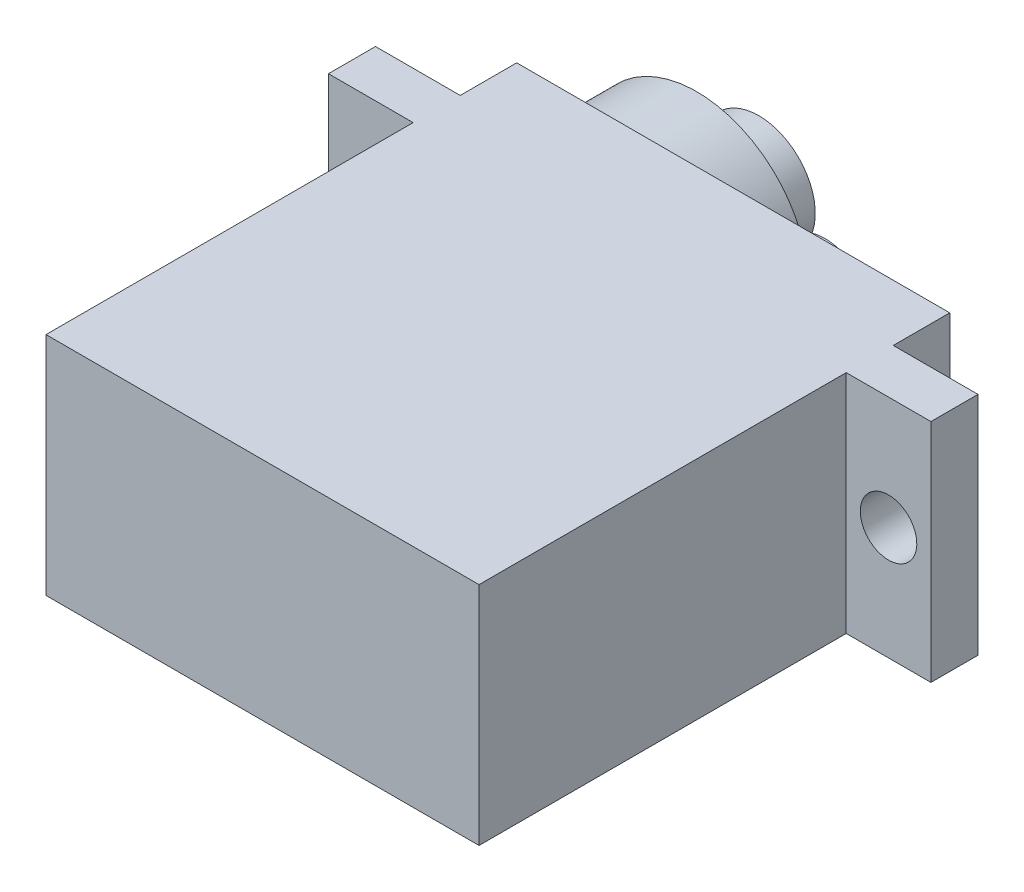
SolidWorks part; units mm, degrees
ref_plane "Front Plane" through (0, 0, 0) normal (0, 0, 1) x (1, 0, 0)
ref_plane "Top Plane" through (0, 0, 0) normal (0, 1, 0) x (1, 0, 0)
ref_plane "Right Plane" through (0, 0, 0) normal (1, 0, 0) x (0, 0, -1)
sketch "Sketch1" plane through (0, 0, 0) normal (0, 0, 1) x (1, 0, 0)
  line L1 (11.5, -6) -> (-11.5, -6)
  line L2 (11.5, -6) -> (11.5, 6)
  line L3 (11.5, 6) -> (-11.5, 6)
  line L4 (-11.5, -6) -> (-11.5, 6)
  line L5 (11.5, -6) -> (-11.5, 6) construction
  line L6 (11.5, 6) -> (-11.5, -6) construction
  point P0 (0, 0)
  dimension "D1" = 23
  dimension "D2" = 12
extrude "Boss-Extrude1" add sketch "Sketch1" along normal blind 25
sketch "Sketch3" plane through (11.5, 0, 0) normal (1, 0, 0) x (0, 0, -1)
  line L0 (-25, 6) -> (0, 6) construction
  line L1 (-3, 6) -> (-5.5, 6)
  line L2 (-3, 6) -> (-3, -6)
  line L3 (-3, -6) -> (-5.5, -6)
  line L4 (-5.5, 6) -> (-5.5, -6)
  line L5 (-25, -6) -> (0, -6) construction
  dimension "D1" = 2.5
  dimension "D2" = 19.5
extrude "Boss-Extrude2" add sketch "Sketch3" along normal blind 4.5
sketch "Sketch4" plane through (-11.5, 0, 0) normal (-1, 0, 0) x (0, 0, 1)
  line L0 (25, 6) -> (0, 6) construction
  line L1 (5.5, 6) -> (3, 6)
  line L2 (5.5, 6) -> (5.5, -6)
  line L3 (5.5, -6) -> (3, -6)
  line L4 (3, 6) -> (3, -6)
  line L5 (25, -6) -> (0, -6) construction
  dimension "D1" = 19.5
  dimension "D2" = 2.5
extrude "Boss-Extrude3" add sketch "Sketch4" along normal blind 4.5
sketch "Sketch5" plane through (0, 0, 0) normal (0, 0, -1) x (-1, 0, 0)
  circle A0 centre (5.443, 0) radius 5.9554
  circle A1 centre (-1.3696, 0.1346) radius 2.4728
  circle A2 centre (5.443, 0) radius 1.9661
extrude "Boss-Extrude13" add sketch "Sketch5" along normal blind 3.5 contours A0 A1 | A1 A0 A2 | A0 A1 | A2
sketch "Sketch7" plane through (0, 0, -3.5) normal (0, 0, -1) x (-1, 0, 0)
  circle A0 centre (5.6429, 0) radius 3
extrude "Boss-Extrude14" add sketch "Sketch7" along normal blind 3.5
sketch "Sketch8" plane through (0, 0, 3) normal (0, 0, -1) x (-1, 0, 0)
  line L4 (13.75, 6) -> (13.75, -7.1508) construction
  line L5 (16, 6) -> (11.5, 6) construction
  line L6 (11.3984, 0) -> (16.9242, 0) construction
  line L9 (-13.75, 6) -> (-13.75, -6.9765) construction
  line L10 (-16, 6) -> (-11.5, 6) construction
  line L13 (-16, -6) -> (-11.5, -6) construction
  arc A1 (-0.1588, -2.0215) -> (-0.0746, 2.2413) centre (5.443, 0) ccw construction
  arc A2 (-0.1588, -2.0215) -> (-0.0746, 2.2413) centre (5.443, 0) ccw construction
  circle A3 centre (13.75, 0) radius 1.5
  circle A4 centre (-13.75, 0) radius 1.5
  dimension "D1" = 6
  dimension "D2" = 3
  dimension "D3" = 3
extrude "Cut-Extrude1" cut sketch "Sketch8" against normal blind 3.5 contours A3 | A4
sketch "Sketch9" plane through (0, -6, 0) normal (0, -1, 0) x (-1, 0, 0)
  line L0 (-8.3308, -10.3562) -> (9.0948, -10.3562) construction
  text T0 "<b>Servo-Motor</b>" font "Century Gothic" height 3.5
extrude "Cut-Extrude2" cut sketch "Sketch9" against normal blind 3.5
sketch "Sketch10" plane through (0, -6, 0) normal (0, -1, 0) x (-1, 0, 0)
  line L0 (-10.0608, -19.0138) -> (10.0778, -19.0138) construction
  text T0 "Team:<b> C1</b>" font "Century Gothic" height 3.5
extrude "Cut-Extrude3" cut sketch "Sketch10" against normal blind 3.5
